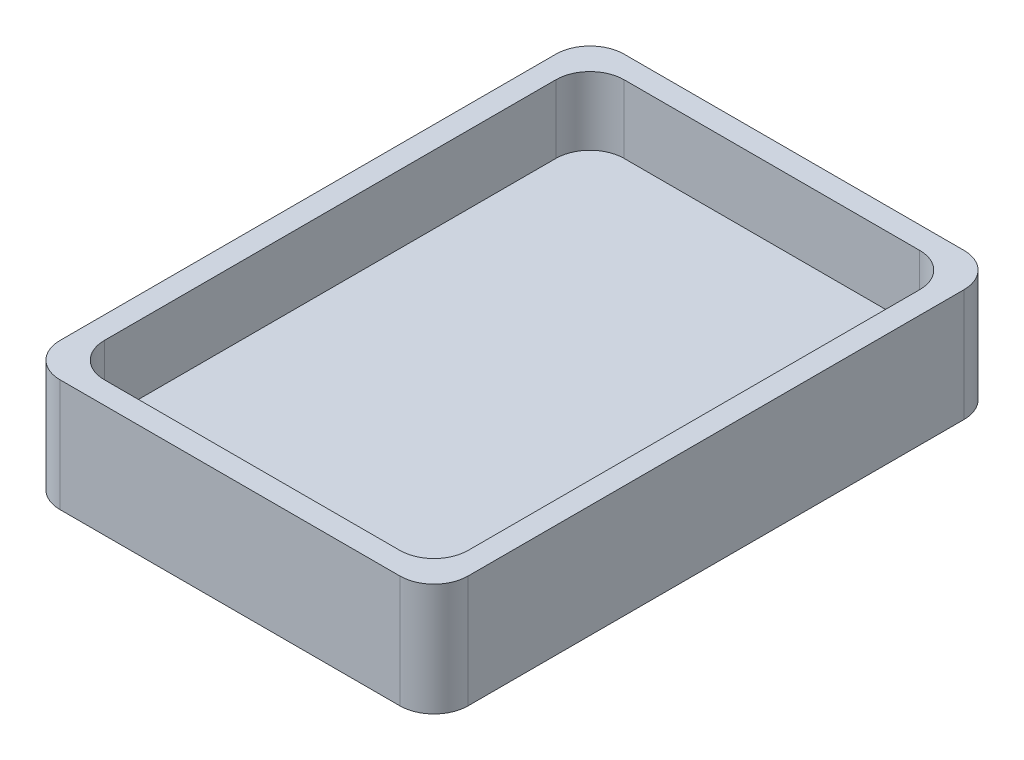
SolidWorks part; units mm, degrees
material "PLA"
ref_plane "Alzado" through (0, 0, 0) normal (0, 0, 1) x (1, 0, 0)
ref_plane "Planta" through (0, 0, 0) normal (0, 1, 0) x (1, 0, 0)
ref_plane "Vista lateral" through (0, 0, 0) normal (1, 0, 0) x (0, 0, -1)
sketch "Croquis1" plane through (0, 0, 0) normal (0, 1, 0) x (1, 0, 0)
  line L1 (-6.9958, 13.8297) -> (10.35, 13.8297)
  line L2 (-8.9958, 11.8297) -> (-8.9958, -14.6703)
  line L3 (-6.9958, -16.6703) -> (10.35, -16.6703)
  line L4 (12.35, 11.8297) -> (12.35, -14.6703)
  line L5 (-8.2958, 15.1297) -> (11.65, 15.1297)
  line L6 (-10.2958, 13.1297) -> (-10.2958, -15.9703)
  line L7 (-8.2958, -17.9703) -> (11.65, -17.9703)
  line L8 (13.65, 13.1297) -> (13.65, -15.9703)
  arc A0 (-8.9958, -14.6703) -> (-6.9958, -16.6703) centre (-6.9958, -14.6703) ccw
  arc A1 (10.35, -16.6703) -> (12.35, -14.6703) centre (10.35, -14.6703) ccw
  arc A2 (10.35, 13.8297) -> (12.35, 11.8297) centre (10.35, 11.8297) cw
  arc A3 (-6.9958, 13.8297) -> (-8.9958, 11.8297) centre (-6.9958, 11.8297) ccw
  arc A4 (-10.2958, -15.9703) -> (-8.2958, -17.9703) centre (-8.2958, -15.9703) ccw
  arc A5 (11.65, -17.9703) -> (13.65, -15.9703) centre (11.65, -15.9703) ccw
  arc A6 (11.65, 15.1297) -> (13.65, 13.1297) centre (11.65, 13.1297) cw
  arc A7 (-8.2958, 15.1297) -> (-10.2958, 13.1297) centre (-8.2958, 13.1297) ccw
  point P12 (12.35, -16.6703)
  point P15 (12.35, 13.8297)
  point P18 (-8.9958, 13.8297)
  dimension "D7" = 2
  dimension "D8" = 2
  dimension "D1" = 21.3458
  dimension "D2" = 1.3
  dimension "D3" = 30.5
  dimension "D4" = 1.3
  dimension "D5" = 1.3
  dimension "D6" = 1.3
extrude "Saliente-Extruir1" add sketch "Croquis1" along normal blind 4
sketch "Croquis2" plane through (0, 0, 0) normal (0, -1, 0) x (1, 0, 0)
  line L4 (-8.2958, -15.1297) -> (11.65, -15.1297)
  line L5 (13.65, -13.1297) -> (13.65, 15.9703)
  line L6 (11.65, 17.9703) -> (-8.2958, 17.9703)
  line L7 (-10.2958, 15.9703) -> (-10.2958, -13.1297)
  line L8 (-8.2958, -15.1297) -> (11.65, -15.1297)
  line L9 (13.65, -13.1297) -> (13.65, 15.9703)
  line L10 (11.65, 17.9703) -> (-8.2958, 17.9703)
  line L11 (-10.2958, 15.9703) -> (-10.2958, -13.1297)
  arc A4 (11.65, -15.1297) -> (13.65, -13.1297) centre (11.65, -13.1297) ccw
  arc A5 (13.65, 15.9703) -> (11.65, 17.9703) centre (11.65, 15.9703) ccw
  arc A6 (-8.2958, 17.9703) -> (-10.2958, 15.9703) centre (-8.2958, 15.9703) ccw
  arc A7 (-10.2958, -13.1297) -> (-8.2958, -15.1297) centre (-8.2958, -13.1297) ccw
  arc A8 (11.65, -15.1297) -> (13.65, -13.1297) centre (11.65, -13.1297) ccw
  arc A9 (13.65, 15.9703) -> (11.65, 17.9703) centre (11.65, 15.9703) ccw
  arc A10 (-8.2958, 17.9703) -> (-10.2958, 15.9703) centre (-8.2958, 15.9703) ccw
  arc A11 (-10.2958, -13.1297) -> (-8.2958, -15.1297) centre (-8.2958, -13.1297) ccw
  dimension "D1" = 0
extrude "Saliente-Extruir2" add sketch "Croquis2" along normal blind 2.6
sketch "Croquis4" plane through (0, -2.6, 0) normal (0, -1, 0) x (1, 0, 0)
  line L0 (1.6771, 17.9703) -> (1.6771, -15.1297) construction
  line L1 (11.65, 17.9703) -> (-8.2958, 17.9703) construction
  line L2 (-8.2958, -15.1297) -> (11.65, -15.1297) construction
  line L4 (-0.5243, 17.9703) -> (-0.5243, -15.1297) construction
  line L5 (13.65, -13.1297) -> (13.65, 15.9703) construction
  text T0 "Z-SCAN" font "Times New Roman" height 4.4028
  point P9 (1.6771, 17.9703)
  dimension "D2" = 13.65
  dimension "D3" = 15.1297
  dimension "D4" = 31.1
extrude "Cortar-Extruir2" cut sketch "Croquis4" against normal blind 1.3
